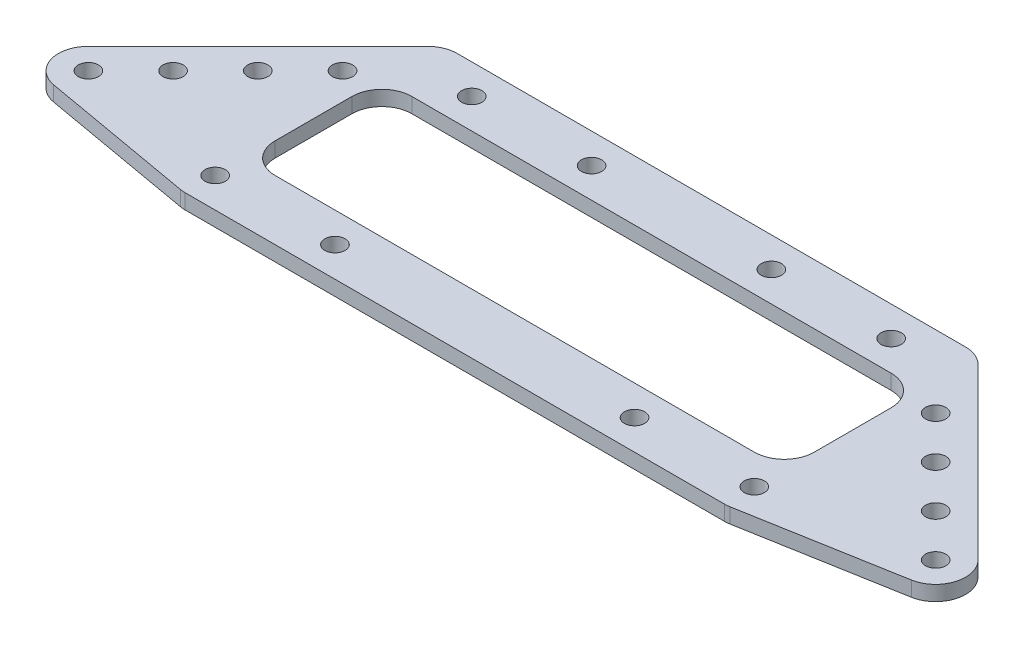
SolidWorks part; units mm, degrees
ref_plane "Front Plane" through (0, 0, 0) normal (0, 0, 1) x (1, 0, 0)
ref_plane "Top Plane" through (0, 0, 0) normal (0, 1, 0) x (1, 0, 0)
ref_plane "Right Plane" through (0, 0, 0) normal (1, 0, 0) x (0, 0, -1)
sketch "Sketch1" plane through (0, 0, 0) normal (0, 1, 0) x (1, 0, 0)
  line L0 (44.45, 0) -> (44.45, -7.0248) construction
  line L1 (98.3315, 6.35) -> (-9.4315, 6.35)
  line L2 (95.25, -6.35) -> (-6.35, -6.35)
  line L3 (-12.7, -12.7) -> (-12.7, -29)
  line L4 (-6.35, -35.35) -> (95.25, -35.35)
  line L5 (0, 0) -> (-37.4363, 0) construction
  line L6 (-9.4315, 0) -> (-60.1279, -50.6964) construction
  line L7 (-49.8427, -31.4309) -> (-13.9217, 4.4901)
  line L8 (-46.4592, -42.1739) -> (-13.8066, -47.9528)
  line L9 (-12.7, -48.05) -> (101.6, -48.05)
  line L10 (101.6, -12.7) -> (101.6, -29)
  line L11 (135.3592, -42.1739) -> (102.7066, -47.9528)
  line L12 (138.7427, -31.4309) -> (102.8217, 4.4901)
  line L13 (110.5803, -12.2487) -> (44.45, 53.8815) construction
  circle A0 centre (0, 0) radius 2.15
  circle A1 centre (25.4, 0) radius 2.15
  circle A2 centre (-18.4118, -8.9803) radius 2.15
  circle A3 centre (-27.392, -17.9605) radius 2.15
  circle A4 centre (-36.3723, -26.9408) radius 2.15
  circle A5 centre (-45.3526, -35.921) radius 2.15
  arc A7 (-9.4315, 6.35) -> (-13.9217, 4.4901) centre (-9.4315, 0) ccw
  arc A8 (-49.8427, -31.4309) -> (-46.4592, -42.1739) centre (-45.3526, -35.921) ccw
  circle A9 centre (-12.7, -41.7) radius 2.15
  arc A10 (-13.8066, -47.9528) -> (-12.7, -48.05) centre (-12.7, -41.7) ccw
  circle A11 centre (12.7, -41.7) radius 2.15
  arc A12 (-6.35, -35.35) -> (-12.7, -29) centre (-6.35, -29) cw
  arc A13 (-12.7, -12.7) -> (-6.35, -6.35) centre (-6.35, -12.7) cw
  arc A14 (95.25, -35.35) -> (101.6, -29) centre (95.25, -29) ccw
  arc A15 (101.6, -12.7) -> (95.25, -6.35) centre (95.25, -12.7) ccw
  circle A16 centre (63.5, 0) radius 2.15
  circle A17 centre (88.9, 0) radius 2.15
  circle A18 centre (107.3118, -8.9803) radius 2.15
  circle A19 centre (116.292, -17.9605) radius 2.15
  circle A20 centre (134.2526, -35.921) radius 2.15
  circle A21 centre (125.2723, -26.9408) radius 2.15
  circle A22 centre (76.2, -41.7) radius 2.15
  circle A23 centre (101.6, -41.7) radius 2.15
  arc A24 (102.7066, -47.9528) -> (101.6, -48.05) centre (101.6, -41.7) cw
  arc A25 (138.7427, -31.4309) -> (135.3592, -42.1739) centre (134.2526, -35.921) cw
  arc A26 (98.3315, 6.35) -> (102.8217, 4.4901) centre (98.3315, 0) cw
  point P16 (-9.4315, 0)
  point P40 (-12.7, -35.35)
  point P43 (-12.7, -6.35)
  point P47 (44.45, -35.35)
  point P50 (44.45, -6.35)
  point P68 (44.45, -48.05)
  point P73 (44.45, 6.35)
  dimension "D1" = 4.3
  dimension "D2" = 4.3
  dimension "D12" = 4.3
  dimension "D17" = 4.3
  dimension "D20" = 4.3
  dimension "D22" = 6.35
  dimension "D10" = 6.35
  dimension "D3" = 25.4
  dimension "D4" = 19.05
  dimension "D5" = 76.2
  dimension "D6" = 6.35
  dimension "D7" = 6.35
  dimension "D8" = 29
  dimension "D9" = 57.15
  dimension "D11" = 45
  dimension "D13" = 12.7
  dimension "D15" = 12.7
  dimension "D16" = 6.35
  dimension "D18" = 6.35
  dimension "D19" = 6.35
  dimension "D21" = 25.4
  dimension "D23" = 90
  dimension "D24" = 31.75
  dimension "D14" = 4
extrude "Boss-Extrude1" add sketch "Sketch1" along normal blind 3.175
